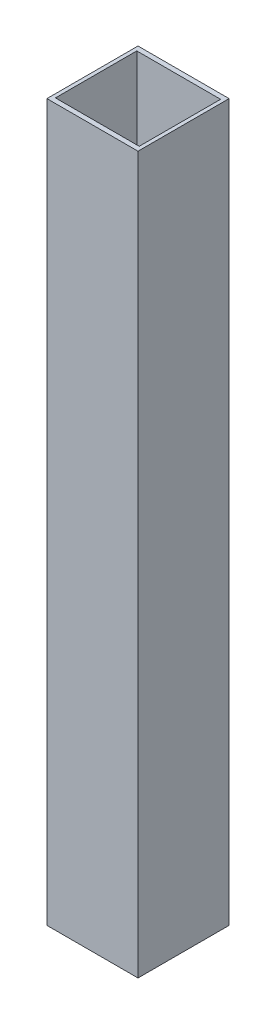
SolidWorks part; units mm, degrees
material "6061 合金"
ref_plane "前视基准面" through (0, 0, 0) normal (0, 0, 1) x (1, 0, 0)
ref_plane "上视基准面" through (0, 0, 0) normal (0, 1, 0) x (1, 0, 0)
ref_plane "右视基准面" through (0, 0, 0) normal (1, 0, 0) x (0, 0, -1)
sketch "草图1" plane through (0, 0, 0) normal (0, 1, 0) x (1, 0, 0)
  line L1 (7.5, -7.5) -> (-7.5, -7.5)
  line L2 (7.5, -7.5) -> (7.5, 7.5)
  line L3 (7.5, 7.5) -> (-7.5, 7.5)
  line L4 (-7.5, -7.5) -> (-7.5, 7.5)
  line L5 (7.5, -7.5) -> (-7.5, 7.5) construction
  line L6 (7.5, 7.5) -> (-7.5, -7.5) construction
  line L7 (6.9, -6.7) -> (-6.9, -6.7)
  line L8 (6.9, -6.7) -> (6.9, 6.7)
  line L9 (6.9, 6.7) -> (-6.9, 6.7)
  line L10 (-6.9, -6.7) -> (-6.9, 6.7)
  line L11 (6.9, -6.7) -> (-6.9, 6.7) construction
  line L12 (6.9, 6.7) -> (-6.9, -6.7) construction
  point P0 (0, 0)
  point P6 (0, 0)
  dimension "D1" = 15
  dimension "D2" = 0.6
  dimension "D3" = 15
  dimension "D4" = 0.8
extrude "凸台-拉伸1" add sketch "草图1" along normal blind 117.91
